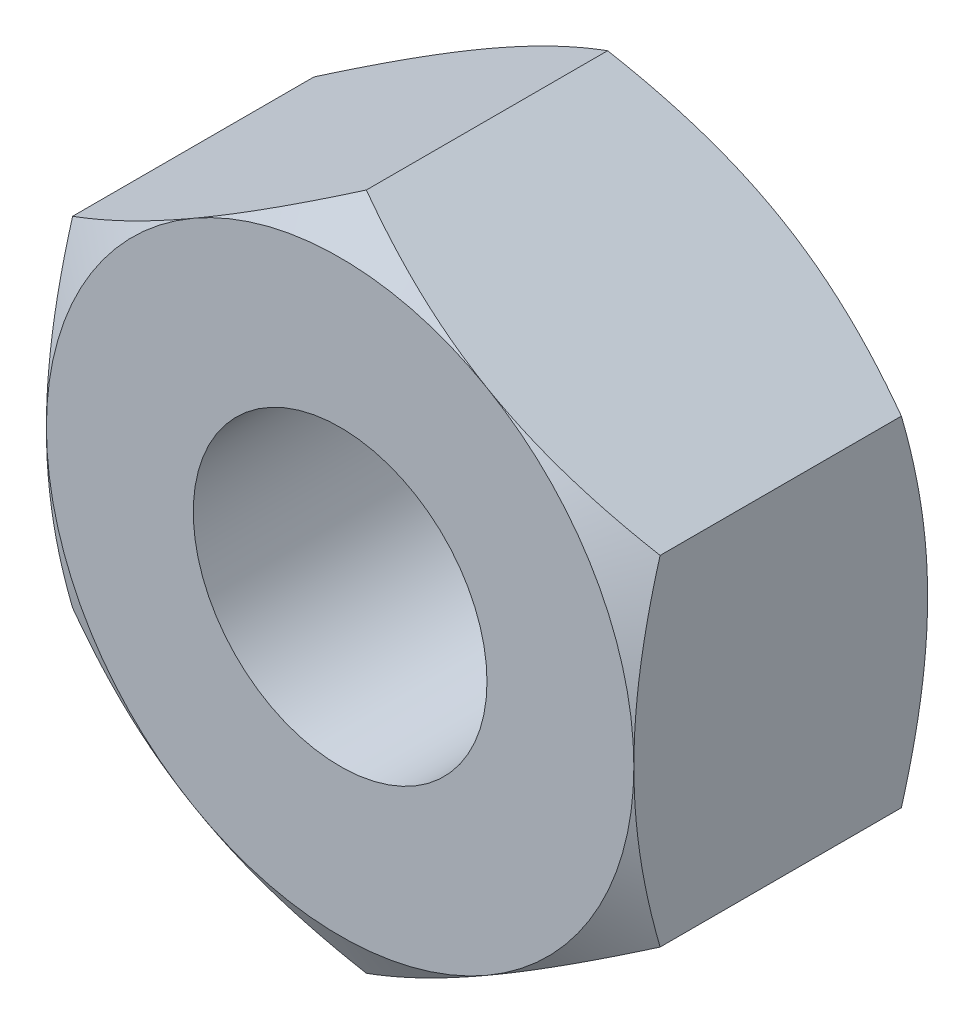
SolidWorks part; units mm, degrees
ref_plane "Front Plane" through (0, 0, 0) normal (0, 0, 1) x (1, 0, 0)
ref_plane "Top Plane" through (0, 0, 0) normal (0, 1, 0) x (1, 0, 0)
ref_plane "Right Plane" through (0, 0, 0) normal (1, 0, 0) x (0, 0, -1)
sketch "Sketch1" plane through (0, 0, 0) normal (0, 0, 1) x (1, 0, 0)
  line L7 (0, 13.8564) -> (-12, 6.9282)
  line L8 (-12, 6.9282) -> (-12, -6.9282)
  line L9 (-12, -6.9282) -> (0, -13.8564)
  line L10 (0, -13.8564) -> (12, -6.9282)
  line L11 (12, -6.9282) -> (12, 6.9282)
  line L12 (12, 6.9282) -> (0, 13.8564)
  circle A0 centre (0, 0) radius 12 construction
  circle A1 centre (0, 0) radius 6
  dimension "D2" = 12
  dimension "D3" = 24
  dimension "D1" = 24
extrude "Boss-Extrude1" add sketch "Sketch1" along normal blind 12
sketch "Sketch3" plane through (0, 0, 0) normal (0, 0, -1) x (-1, 0, 0)
  circle A0 centre (0, 0) radius 12
  dimension "D1" = 24
extrude "Cut-Extrude1" cut sketch "Sketch3" against normal blind 35 draft 60 flip side to cut
sketch "Sketch4" plane through (0, 0, 12) normal (0, 0, 1) x (1, 0, 0)
  circle A0 centre (0, 0) radius 12
  dimension "D1" = 24
extrude "Cut-Extrude2" cut sketch "Sketch4" against normal blind 35 draft 60 flip side to cut
